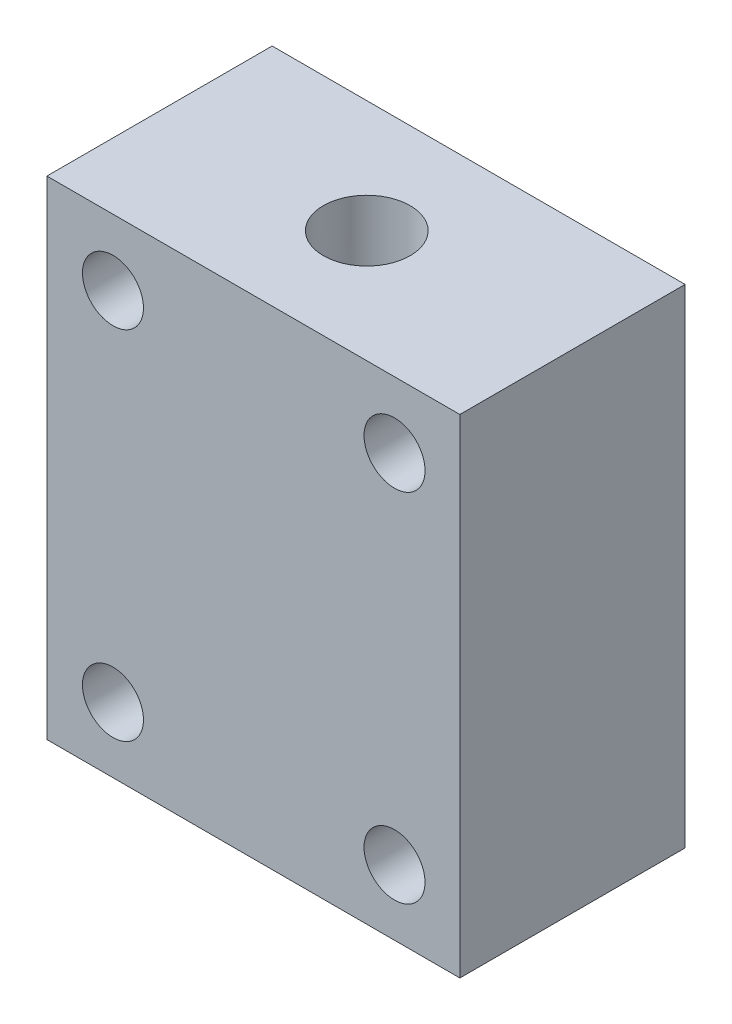
SolidWorks part; units mm, degrees
ref_plane "Front Plane" through (0, 0, 0) normal (1, 0, 0) x (0, 1, 0)
ref_plane "Top Plane" through (0, 0, 0) normal (0, 0, 1) x (0, 1, 0)
ref_plane "Right Plane" through (0, 0, 0) normal (0, 1, 0) x (-1, 0, 0)
sketch "Sketch1" plane through (0, 0, 0) normal (0, 0, 1) x (0, 1, 0)
  line L1 (-41.275, -34.925) -> (41.275, -34.925)
  line L2 (-41.275, -34.925) -> (-41.275, 34.925)
  line L3 (-41.275, 34.925) -> (41.275, 34.925)
  line L4 (41.275, -34.925) -> (41.275, 34.925)
  line L5 (-41.275, -34.925) -> (41.275, 34.925) construction
  line L6 (-41.275, 34.925) -> (41.275, -34.925) construction
  point P0 (0, 0)
  dimension "D1" = 41.275
  dimension "D2" = 34.925
extrude "Boss-Extrude1" add sketch "Sketch1" along normal mid plane 38.1
hole_wizard "3/8 Clearance Hole1" positions "Sketch3" profile "Sketch2" hole size "3/8" standard "ANSI Inch"
sketch "Sketch3" plane through (0, 0, -19.05) normal (0, 0, -1) x (-1, 0, 0)
  line L0 (-23.876, -30.226) -> (23.749, -30.226) construction
  line L1 (23.749, -30.226) -> (23.749, 30.099) construction
  line L2 (23.749, 30.099) -> (-23.876, 30.099) construction
  line L3 (-23.876, 30.099) -> (-23.876, -30.226) construction
  line L4 (-34.925, -41.275) -> (-34.925, 41.275) construction
  line L5 (-34.925, 41.275) -> (34.925, 41.275) construction
  point P0 (-23.876, -30.226)
  point P1 (-23.876, 30.099)
  point P3 (23.749, -30.226)
  point P5 (23.749, 30.099)
  dimension "D1" = 11.049
  dimension "D2" = 11.049
  dimension "D3" = 58.674
  dimension "D4" = 58.674
  dimension "D5" = 11.176
  dimension "D6" = 11.176
  dimension "D7" = 71.501
  dimension "D8" = 71.501
sketch "Sketch2" plane through (23.876, -30.226, -19.05) normal (1, 0, 0) x (0, 1, 0)
  line L0 (0, 0) -> (0, 41.2001)
  line L1 (0, 41.2001) -> (5.1594, 38.1)
  line L2 (5.1594, 38.1) -> (5.1594, 0)
  line L5 (5.1594, 0) -> (0, 0)
  line L10 (0, 41.2001) -> (-5.1594, 38.1) construction
  line L11 (0, -6.35) -> (0, 107.95) construction
  dimension "Hole Dia." = 10.3187
  dimension "Hole Depth" = 38.1
  dimension "Drill Angle" = 118
sketch "Sketch4" plane through (0, 0, 0) normal (0, 0, 1) x (0, 1, 0)
  circle A0 centre (-17.653, -0.127) radius 7.3422
  circle A1 centre (17.399, -0.127) radius 7.3422
  dimension "D1" = 14.6844
  dimension "D2" = 14.6844
  dimension "D3" = 35.052
extrude "Cut-Extrude2" cut sketch "Sketch4" along normal blind 28.448 from offset 19.05
sketch "Sketch5" plane through (0, 0, 0) normal (0, 0, 1) x (0, 1, 0)
  circle A0 centre (-17.653, -0.127) radius 12.7254
  circle A1 centre (17.399, -0.127) radius 12.7254
  dimension "D1" = 25.4508
  dimension "D2" = 25.4508
  dimension "D3" = 35.052
extrude "Cut-Extrude4" cut sketch "Sketch5" along normal blind 2.8194 from offset 19.05
sketch "Sketch6" plane through (0, 0, 0) normal (0, 1, 0) x (-1, 0, 0)
  circle A0 centre (-0.127, 0) radius 7.3422
  dimension "D1" = 14.6844
extrude "Cut-Extrude6" cut sketch "Sketch6" against normal blind 60.452 from offset 41.275
